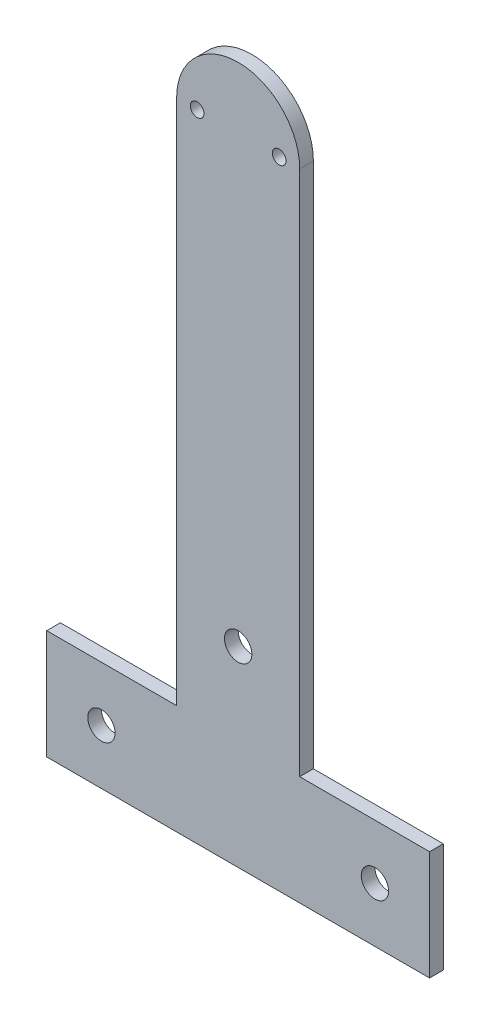
SolidWorks part; units mm, degrees
ref_plane "前视基准面" through (0, 0, 0) normal (0, 0, 1) x (1, 0, 0)
ref_plane "上视基准面" through (0, 0, 0) normal (0, 1, 0) x (1, 0, 0)
ref_plane "右视基准面" through (0, 0, 0) normal (1, 0, 0) x (0, 0, -1)
sketch "草图1" plane through (0, 0, 0) normal (0, 0, 1) x (1, 0, 0)
  line L2 (-13.3404, 27.5655) -> (-13.3404, 112.5655) construction
  line L3 (-13.3404, 112.5655) -> (-7.3404, 112.5655) construction
  line L4 (-22.3404, 112.5655) -> (-22.3404, 35.5655)
  line L6 (14.6596, 19.5655) -> (14.6596, 35.5655)
  line L9 (-41.3404, 19.5655) -> (-41.3404, 35.5655)
  line L11 (-41.3404, 35.5655) -> (-22.3404, 35.5655)
  line L13 (-4.3404, 112.5655) -> (-4.3404, 35.5655)
  line L14 (-33.3404, 27.5655) -> (-13.3404, 27.5655) construction
  line L15 (-13.3404, 27.5655) -> (6.6596, 27.5655) construction
  line L16 (-4.3404, 35.5655) -> (14.6596, 35.5655)
  line L17 (-41.3404, 19.5655) -> (14.6596, 19.5655)
  circle A4 centre (-33.3404, 27.5655) radius 2
  circle A5 centre (6.6596, 27.5655) radius 2
  circle A7 centre (-7.3404, 112.5655) radius 1
  circle A8 centre (-19.3404, 112.5655) radius 1
  circle A9 centre (-13.3404, 112.5655) radius 1.1 construction
  circle A10 centre (-13.3404, 112.5655) radius 9 construction
  arc A11 (-22.3404, 112.5655) -> (-4.3404, 112.5655) centre (-13.3404, 112.5655) cw
  circle A12 centre (-13.3404, 47.5655) radius 2
  dimension "D5" = 18
  dimension "D6" = 2
  dimension "D7" = 4
  dimension "D8" = 65
  dimension "D2" = 20
  dimension "D3" = 8
  dimension "D4" = 8
  dimension "D9" = 8
  dimension "D10" = 20
  dimension "D11" = 20
  dimension "D12" = 8
extrude "凸台-拉伸1" add sketch "草图1" along normal blind 2
